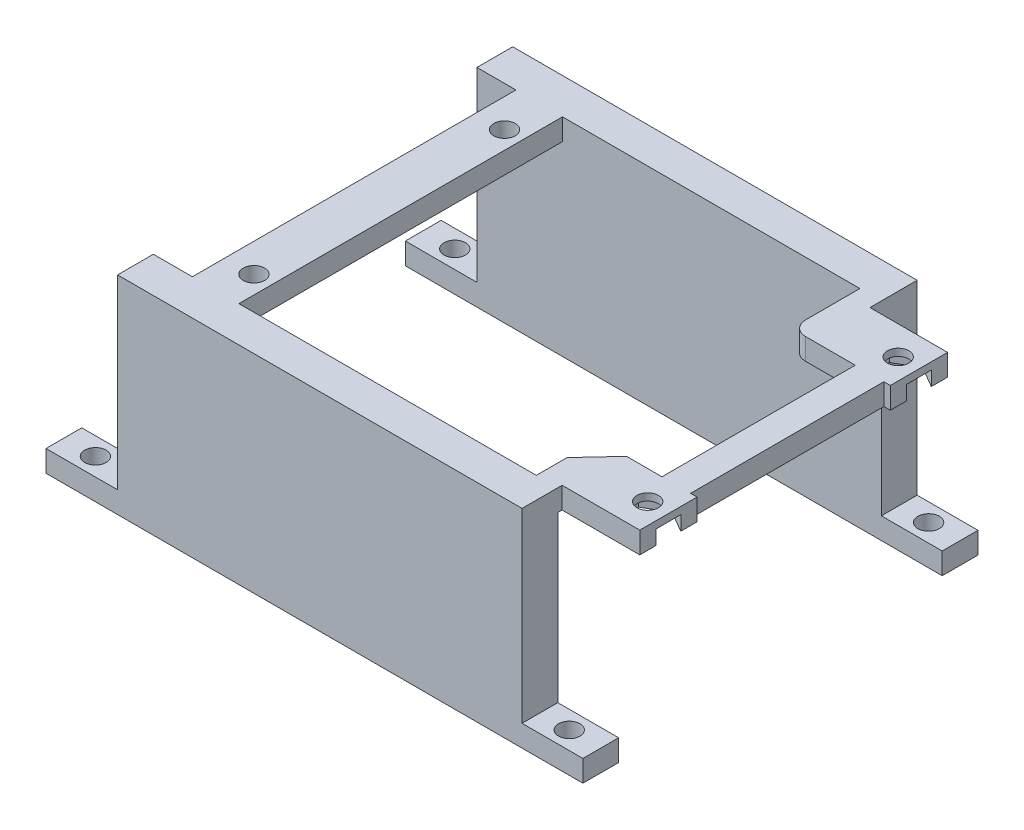
SolidWorks part; units mm, degrees
ref_plane "Płaszczyzna przednia" through (0, 0, 0) normal (0, 0, 1) x (1, 0, 0)
ref_plane "Płaszczyzna górna" through (0, 0, 0) normal (0, 1, 0) x (1, 0, 0)
ref_plane "Płaszczyzna prawa" through (0, 0, 0) normal (1, 0, 0) x (0, 0, -1)
sketch "Szkic1" plane through (0, 0, 0) normal (0, 1, 0) x (1, 0, 0)
  line L0 (-37.5542, 25.1) -> (37.5542, 25.1) construction
  line L1 (-43.8197, 0) -> (52.4271, 0) construction
  line L2 (0, 0) -> (0, 25.1) construction
  line L3 (37.5, 22.6) -> (-37.5, 22.6)
  line L4 (37.5, 22.6) -> (37.5, 27.6)
  line L5 (37.5, 27.6) -> (-37.5, 27.6)
  line L6 (-37.5, 22.6) -> (-37.5, 27.6)
  line L7 (37.5, 22.6) -> (-37.5, 27.6) construction
  line L8 (37.5, 27.6) -> (-37.5, 22.6) construction
  line L9 (37.5, -27.6) -> (-37.5, -22.6) construction
  line L10 (37.5, -22.6) -> (-37.5, -27.6) construction
  line L11 (-37.5542, -25.1) -> (37.5542, -25.1) construction
  line L12 (-37.5, -22.6) -> (-37.5, -27.6)
  line L13 (37.5, -27.6) -> (-37.5, -27.6)
  line L14 (37.5, -22.6) -> (37.5, -27.6)
  line L15 (37.5, -22.6) -> (-37.5, -22.6)
  circle A0 centre (-33.1, 25.1) radius 1.5
  circle A1 centre (33.1, 25.1) radius 1.5
  circle A2 centre (33.1, -25.1) radius 1.5
  circle A3 centre (-33.1, -25.1) radius 1.5
  point P7 (0, 25.1)
  point P8 (0, 25.1)
  point P27 (0, -25.1)
  dimension "D1" = 25.1
  dimension "D4" = 3
  dimension "D2" = 33.1
  dimension "D3" = 75
  dimension "D5" = 5
extrude "Dodanie-wyciągnięcie1" add sketch "Szkic1" along normal blind 29
sketch "Szkic2" plane through (0, 29, 0) normal (0, 1, 0) x (1, 0, 0)
  line L0 (-40.7439, 0) -> (49.0436, 0) construction
  line L1 (-37.5, 22.6) -> (37.5, 22.6) construction
  line L2 (-37.5, 27.6) -> (-27.5, 27.6)
  line L3 (-37.5, 27.6) -> (-37.5, 22.6)
  line L4 (-37.5, 22.6) -> (-27.5, 22.6)
  line L5 (-27.5, 27.6) -> (-27.5, 22.6)
  line L6 (0, -27.6) -> (0, 27.6) construction
  line L7 (-37.5, -27.6) -> (37.5, -27.6) construction
  line L8 (37.5, 27.6) -> (-37.5, 27.6) construction
  line L9 (37.5, 22.6) -> (27.5, 22.6)
  line L10 (27.5, 27.6) -> (27.5, 22.6)
  line L11 (37.5, 27.6) -> (27.5, 27.6)
  line L12 (37.5, 27.6) -> (37.5, 22.6)
  line L13 (37.5, -27.6) -> (37.5, -22.6)
  line L14 (37.5, -27.6) -> (27.5, -27.6)
  line L15 (27.5, -27.6) -> (27.5, -22.6)
  line L16 (37.5, -22.6) -> (27.5, -22.6)
  line L17 (-27.5, -27.6) -> (-27.5, -22.6)
  line L18 (-37.5, -22.6) -> (-27.5, -22.6)
  line L19 (-37.5, -27.6) -> (-37.5, -22.6)
  line L20 (-37.5, -27.6) -> (-27.5, -27.6)
  dimension "D1" = 10
extrude "Wytnij-wyciągnięcie1" cut sketch "Szkic2" against normal blind 26
sketch "Szkic3" plane through (0, 29, 0) normal (0, 1, 0) x (1, 0, 0)
  line L0 (27.5, 27.6) -> (-27.5, 27.6) construction
  line L5 (38.95, 27.6) -> (34.95, 27.6)
  line L6 (38.95, 27.6) -> (38.95, -27.6)
  line L7 (38.95, -27.6) -> (34.95, -27.6)
  line L8 (34.95, 27.6) -> (34.95, -27.6)
  line L9 (-27.5, -27.6) -> (27.5, -27.6) construction
  line L10 (40.95, -37.9519) -> (40.95, 42.2433) construction
  line L11 (-22.05, 27.6) -> (-14.05, 27.6)
  line L12 (-22.05, 27.6) -> (-22.05, -27.6)
  line L13 (-22.05, -27.6) -> (-14.05, -27.6)
  line L14 (-14.05, 27.6) -> (-14.05, -27.6)
  line L15 (-25.25, 42.2433) -> (-25.25, -39.4271) construction
  line L16 (-50.1404, -20.5) -> (57.4409, -20.5) construction
  line L17 (57.4409, 20.5) -> (-49.3153, 20.5) construction
  circle A0 centre (-18.05, -18) radius 1.5
  circle A2 centre (-33.1, -25.1) radius 1.5 construction
  circle A3 centre (36.95, -18) radius 1.5
  circle A4 centre (-18.05, 17) radius 1.5
  circle A5 centre (36.95, 17) radius 1.5
  circle A6 centre (33.1, -25.1) radius 1.5 construction
  dimension "D3" = 7.85
  dimension "D6" = 3
  dimension "D10" = 55
  dimension "D13" = 35
  dimension "D14" = 4
  dimension "D2" = 7.85
  dimension "D4" = 2
  dimension "D5" = 2
  dimension "D7" = 41
  dimension "D8" = 20.5
  dimension "D9" = 2.5
  dimension "D11" = 4
  dimension "D12" = 8
extrude "Dodanie-wyciągnięcie6" add sketch "Szkic3" against normal blind 3
sketch "Szkic8" plane through (0, 29, 0) normal (0, 1, 0) x (1, 0, 0)
  line L0 (29, 27.6) -> (26, 27.6)
  line L1 (34.95, 27.6) -> (34.95, -27.6) construction
  line L2 (37.5, 27.6) -> (27.5, 27.6) construction
  line L3 (27.5, 27.6) -> (-27.5, 27.6) construction
  line L4 (26, 27.6) -> (26, 13)
  line L5 (26, 13) -> (32.95, 13)
  line L6 (32.95, 13) -> (32.95, 21)
  line L7 (32.95, 21) -> (29, 21)
  line L8 (32.95, 13) -> (40.95, 13)
  line L9 (32.95, 13) -> (32.95, 21)
  line L10 (32.95, 21) -> (40.95, 21)
  line L11 (40.95, 13) -> (40.95, 21)
  line L12 (32.95, 13) -> (40.95, 21) construction
  line L13 (32.95, 21) -> (40.95, 13) construction
  line L14 (-14.05, 0) -> (34.95, 0) construction
  line L15 (-14.05, -22.6) -> (-14.05, 22.6) construction
  line L16 (29, 21) -> (29, 27.6)
  line L17 (32.95, -22) -> (40.95, -22)
  line L22 (27.5, 27.6) -> (27.5, 22.6) construction
  line L23 (32.95, -22) -> (29, -22)
  line L24 (29, -22) -> (29, -27.6)
  line L25 (29, -27.6) -> (26, -27.6)
  line L26 (32.95, -14) -> (26, -14)
  line L27 (32.95, -22) -> (32.95, -14)
  line L28 (32.95, -14) -> (40.95, -14)
  line L29 (40.95, -22) -> (40.95, -14)
  line L30 (32.95, -22) -> (40.95, -14) construction
  line L31 (32.95, -14) -> (40.95, -22) construction
  line L32 (26, -14) -> (26, -27.6)
  point P4 (36.95, 17)
  point P23 (36.95, -18)
  point P33 (36.95, -17)
  dimension "D1" = 8
  dimension "D2" = 1.5
  dimension "D3" = 1.5
  dimension "D5" = 8
extrude "Dodanie-wyciągnięcie7" add sketch "Szkic8" against normal blind 3
sketch "Szkic9" plane through (0, 29, 0) normal (0, 1, 0) x (1, 0, 0)
  line L1 (34.95, 27.6) -> (38.95, 27.6)
  line L2 (34.95, 27.6) -> (34.95, 21)
  line L3 (34.95, 21) -> (38.95, 21)
  line L4 (38.95, 27.6) -> (38.95, 21)
  line L5 (34.95, -27.6) -> (38.95, -27.6)
  line L6 (34.95, -27.6) -> (34.95, -22)
  line L7 (34.95, -22) -> (38.95, -22)
  line L8 (38.95, -27.6) -> (38.95, -22)
extrude "Wytnij-wyciągnięcie3" cut sketch "Szkic9" against normal up to next
sketch "Szkic10" plane through (0, 26, 0) normal (0, -1, 0) x (1, 0, 0)
  line L13 (36.95, -13.5936) -> (34, -15.2968)
  line L14 (34, -15.2968) -> (34, -18.7032)
  line L15 (34, -18.7032) -> (36.95, -20.4064)
  line L16 (36.95, -20.4064) -> (39.9, -18.7032)
  line L17 (39.9, -18.7032) -> (39.9, -15.2968)
  line L18 (39.9, -15.2968) -> (36.95, -13.5936)
  line L19 (36.95, 21.4064) -> (34, 19.7032)
  line L20 (34, 19.7032) -> (34, 16.2968)
  line L21 (34, 16.2968) -> (36.95, 14.5936)
  line L22 (36.95, 14.5936) -> (39.9, 16.2968)
  line L23 (39.9, 16.2968) -> (39.9, 19.7032)
  line L24 (39.9, 19.7032) -> (36.95, 21.4064)
  circle A2 centre (36.95, -17) radius 2.95 construction
  circle A3 centre (36.95, 18) radius 2.95 construction
  dimension "D3" = 5.9
  dimension "D4" = 5.9
extrude "Wytnij-wyciągnięcie4" cut sketch "Szkic10" against normal blind 2
sketch "Szkic11" plane through (0, 29, 0) normal (0, 1, 0) x (1, 0, 0)
  line L0 (29, -22) -> (40.95, -22) construction
  line L1 (40.95, 21) -> (39.85, 21)
  line L2 (40.95, 21) -> (40.95, -22)
  line L3 (40.95, -22) -> (39.85, -22)
  line L4 (39.85, 21) -> (39.85, -22)
  dimension "D1" = 1.1
extrude "Wytnij-wyciągnięcie5" cut sketch "Szkic11" against normal up to next
sketch "Szkic12" plane through (27.5, 0, 0) normal (1, 0, 0) x (0, 0, -1)
  line L0 (22.6, 3) -> (27.6, 3) construction
  line L1 (-27.6, 3) -> (-22.6, 3)
  line L2 (-27.6, 3) -> (-27.6, 26)
  line L3 (-27.6, 26) -> (-22.6, 26)
  line L4 (-22.6, 3) -> (-22.6, 26)
  line L5 (22.6, 26) -> (27.6, 26)
  line L6 (22.6, 26) -> (22.6, 3)
  line L7 (22.6, 3) -> (27.6, 3)
  line L8 (27.6, 26) -> (27.6, 3)
  line L9 (27.6, 3) -> (22.6, 3) construction
  line L10 (27.6, 3) -> (27.6, 26) construction
extrude "Dodanie-wyciągnięcie8" add sketch "Szkic12" along normal up to surface (1.5 mm away) up to face at (29, 27.5, 24.8)
sketch "Szkic13" plane through (0, 29, 0) normal (0, 1, 0) x (1, 0, 0)
  line L0 (26, -14) -> (30, -14)
  line L1 (26, -14) -> (34.95, -14) construction
  line L2 (30, -14) -> (26, -18.3)
  line L3 (26, -14) -> (26, -22.6) construction
  line L4 (26, -18.3) -> (26, -14)
  dimension "D1" = 4
extrude "Wytnij-wyciągnięcie6" cut sketch "Szkic13" against normal up to next
fillet "Zaokrąglenie1" radius 2 1 edges at (26, 27.5, -13)
sketch "Szkic14" plane through (0, 29, 0) normal (0, 1, 0) x (1, 0, 0)
  line L0 (26, -22.6) -> (-14.05, -22.6) construction
  line L1 (-14.05, 22.6) -> (-15.55, 22.6)
  line L2 (-14.05, 22.6) -> (-14.05, -22.6)
  line L3 (-14.05, -22.6) -> (-15.55, -22.6)
  line L4 (-15.55, 22.6) -> (-15.55, -22.6)
  dimension "D1" = 1.5
extrude "Wytnij-wyciągnięcie7" cut sketch "Szkic14" against normal up to next
